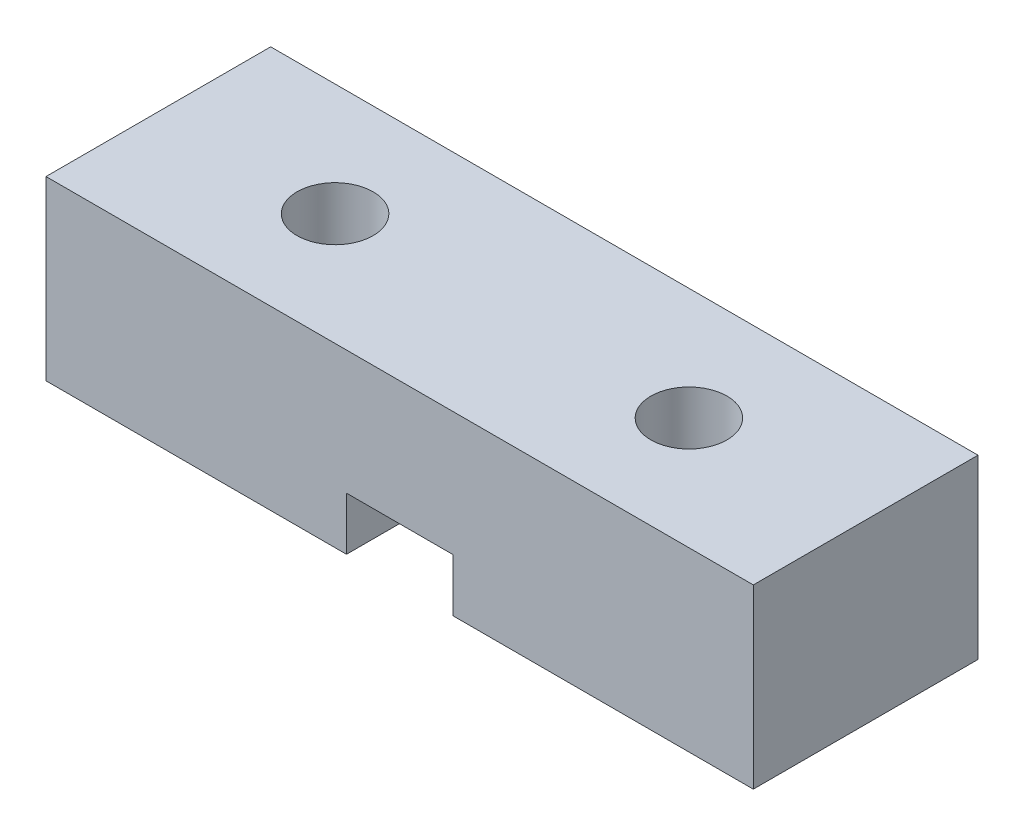
SolidWorks part; units mm, degrees
material "6061-T6 (SS)"
ref_plane "Front Plane" through (0, 0, 0) normal (0, 0, 1) x (1, 0, 0)
ref_plane "Top Plane" through (0, 0, 0) normal (0, 1, 0) x (1, 0, 0)
ref_plane "Right Plane" through (0, 0, 0) normal (1, 0, 0) x (0, 0, -1)
sketch "Sketch1" plane through (0, 0, 0) normal (0, 0, 1) x (1, 0, 0)
  line L0 (-65, 30) -> (-65, 10) construction
  line L1 (-74.5, 40) -> (74.5, 40)
  line L2 (-74.5, 40) -> (-74.5, 0)
  line L3 (-74.5, 0) -> (74.5, 0)
  line L4 (74.5, 40) -> (74.5, 0)
  line L5 (31.995, 22.86) -> (38.005, 22.86)
  line L6 (31.995, 22.86) -> (31.995, 16.85)
  line L7 (31.995, 16.85) -> (38.005, 16.85)
  line L8 (38.005, 22.86) -> (38.005, 16.85)
  line L9 (32, 22.855) -> (38, 22.855) construction
  line L10 (32, 22.855) -> (32, 16.855) construction
  line L11 (32, 16.855) -> (38, 16.855) construction
  line L12 (38, 22.855) -> (38, 16.855) construction
  line L13 (0, 0) -> (0, 40) construction
  line L14 (38.005, 19.855) -> (55, 19.855) construction
  line L15 (31.995, 19.855) -> (15, 19.855) construction
  line L16 (15, 19.855) -> (15, 40) construction
  line L17 (55, 19.855) -> (55, 40) construction
  line L18 (31.995, 19.865) -> (15.01, 19.865)
  line L19 (15.01, 19.865) -> (15.01, 40)
  line L20 (38.005, 19.865) -> (54.99, 19.865)
  line L21 (54.99, 19.865) -> (54.99, 40)
  line L22 (15.01, 29.865) -> (54.99, 29.865)
  circle A0 centre (-65, 30) radius 2.5 construction
  circle A1 centre (-65, 10) radius 2.5 construction
  circle A2 centre (65, 10) radius 2.5 construction
  circle A3 centre (65, 30) radius 2.5 construction
  point P10 (0, 0)
  point P14 (35, 22.855)
  point P15 (35, 22.86)
  point P16 (32, 19.855)
  point P17 (31.995, 19.855)
  point P34 (38.005, 19.855)
  point P43 (0, 0)
  dimension "D8" = 5
  dimension "D1" = 6.01
  dimension "D2" = 149
  dimension "D3" = 40
  dimension "D4" = 16.85
  dimension "D5" = 32
  dimension "D6" = 6
  dimension "D7" = 20
  dimension "D9" = 10
  dimension "D10" = 65
  dimension "D11" = 40
  dimension "D14" = 10
  dimension "D12" = 0.01
  dimension "D13" = 0.01
extrude "Boss-Extrude1" add sketch "Sketch1" against normal blind 12.7 contours L20 L21 L1 L19 L18 L6 L5 L8
sketch "Sketch2" plane through (0, 19.865, 0) normal (0, -1, 0) x (1, 0, 0)
  line L0 (54.99, 0) -> (38.005, 0) construction
  line L1 (38.005, 0) -> (38.005, -12.7) construction
  line L2 (38.005, -12.7) -> (54.99, -12.7) construction
  line L3 (54.99, -12.7) -> (54.99, 0) construction
  line L4 (31.995, 0) -> (15.01, 0) construction
  line L5 (15.01, 0) -> (15.01, -12.7) construction
  line L6 (15.01, -12.7) -> (31.995, -12.7) construction
  line L7 (31.995, -12.7) -> (31.995, 0) construction
  line L8 (54.99, 0) -> (38.005, 0)
  line L9 (38.005, 0) -> (38.005, -12.7)
  line L10 (38.005, -12.7) -> (54.99, -12.7)
  line L11 (54.99, -12.7) -> (54.99, 0)
  line L12 (31.995, 0) -> (15.01, 0)
  line L13 (15.01, 0) -> (15.01, -12.7)
  line L14 (15.01, -12.7) -> (31.995, -12.7)
  line L15 (31.995, -12.7) -> (31.995, 0)
  line L16 (25, -6.35) -> (45, -6.35)
  line L17 (31.995, 0) -> (38.005, 0)
  circle A0 centre (25, -6.35) radius 2 construction
  circle A1 centre (45, -6.35) radius 2 construction
  point P10 (15.01, -6.35)
  point P12 (35, 0)
  point P14 (35, -6.35)
  dimension "D2" = 4
  dimension "D4" = 9.99
  dimension "D1" = 20
  dimension "D3" = 9.99
hole_wizard "M4 Clearance Hole1" positions "3DSketch1" profile "Sketch3" hole size "M4" standard "ANSI Metric" end condition up to next
sketch3d "3DSketch1"
  point P0 (25, 19.865, -6.35)
  point P2 (45, 19.865, -6.35)
  point P5 (46.505, 19.865, -6.35)
  point P7 (23.495, 19.865, -6.35)
sketch "Sketch3" plane through (25, 19.865, -6.35) normal (1, 0, 0) x (0, 0, -1)
  line L0 (0, 0) -> (0, 10)
  line L1 (0, 10) -> (2.15, 10)
  line L2 (2.15, 10) -> (2.15, 0)
  line L5 (2.15, 0) -> (0, 0)
  line L11 (0, -6.35) -> (0, 107.95) construction
  dimension "Thru Hole Dia." = 4.3
  dimension "Thru Hole Depth" = 10
